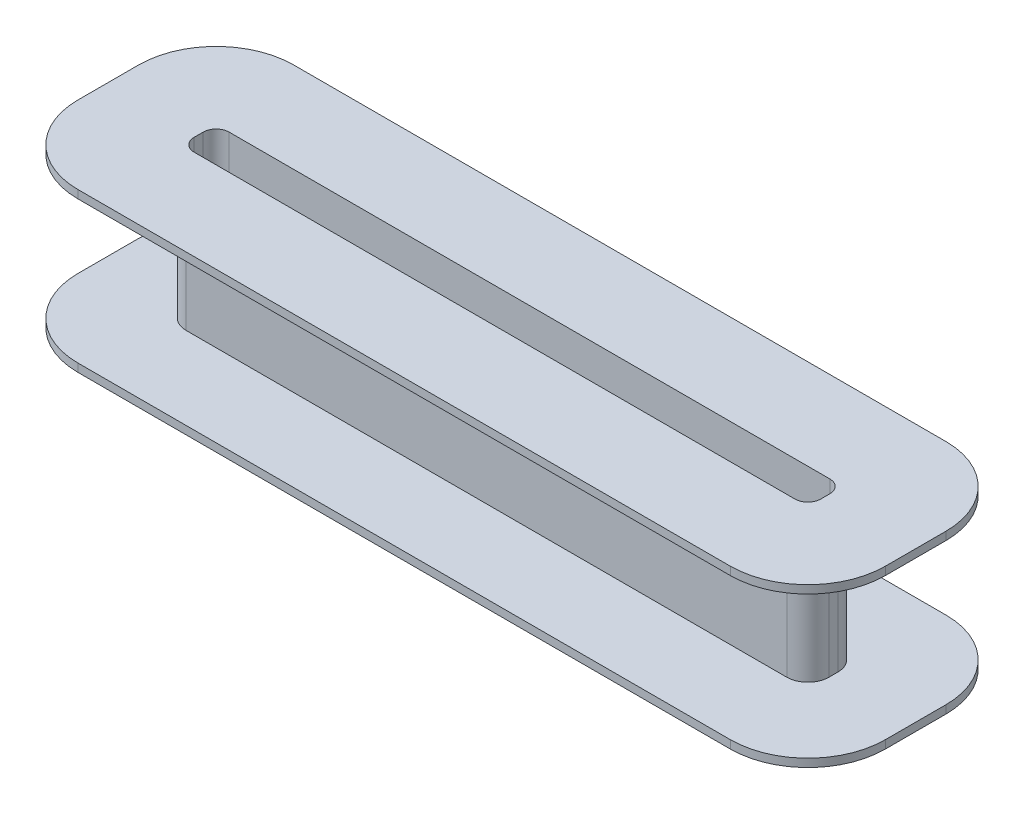
SolidWorks part; units mm, degrees
ref_plane "Front Plane" through (0, 0, 0) normal (0, 0, 1) x (1, 0, 0)
ref_plane "Top Plane" through (0, 0, 0) normal (0, 1, 0) x (1, 0, 0)
ref_plane "Right Plane" through (0, 0, 0) normal (1, 0, 0) x (0, 0, -1)
sketch "Sketch1" plane through (0, 0, 0) normal (0, 1, 0) x (1, 0, 0)
  line L1 (-30.7975, -1.7145) -> (30.7975, -1.7145)
  line L2 (-30.7975, -1.7145) -> (-30.7975, 1.7145)
  line L3 (-30.7975, 1.7145) -> (30.7975, 1.7145)
  line L4 (30.7975, -1.7145) -> (30.7975, 1.7145)
  line L5 (-30.7975, -1.7145) -> (30.7975, 1.7145) construction
  line L6 (-30.7975, 1.7145) -> (30.7975, -1.7145) construction
  line L7 (-39.6875, -10.6045) -> (39.6875, -10.6045)
  line L8 (-39.6875, -10.6045) -> (-39.6875, 10.6045)
  line L9 (-39.6875, 10.6045) -> (39.6875, 10.6045)
  line L10 (39.6875, -10.6045) -> (39.6875, 10.6045)
  line L11 (-39.6875, -10.6045) -> (39.6875, 10.6045) construction
  line L12 (-39.6875, 10.6045) -> (39.6875, -10.6045) construction
  point P0 (0, 0)
  point P6 (0, 0)
  dimension "D1" = 3.429
  dimension "D2" = 8.89
  dimension "D3" = 8.89
  dimension "D4" = 61.595
extrude "Boss-Extrude1" add sketch "Sketch1" along normal blind 0.8
fillet "Fillet1" radius 1.27 4 edges at (30.7975, 0.4, -1.7145) (30.7975, 0.4, 1.7145) (-30.7975, 0.4, -1.7145) (-30.7975, 0.4, 1.7145)
fillet "Fillet2" radius 7.62 4 edges at (39.6875, 0.4, 10.6045) (39.6875, 0.4, -10.6045) (-39.6875, 0.4, 10.6045) (-39.6875, 0.4, -10.6045)
sketch "Sketch2" plane through (0, 0.8, 0) normal (0, 1, 0) x (1, 0, 0)
  line L0 (29.5275, 1.7145) -> (-29.5275, 1.7145) construction
  line L2 (30.7975, -0.4445) -> (30.7975, 0.4445) construction
  line L8 (-29.5275, -1.7145) -> (29.5275, -1.7145) construction
  line L14 (-30.7975, 0.4445) -> (-30.7975, -0.4445) construction
  line L26 (30.7975, -0.4445) -> (30.7975, 0.4445)
  line L27 (-29.5275, -1.7145) -> (29.5275, -1.7145)
  line L28 (-30.7975, 0.4445) -> (-30.7975, -0.4445)
  line L29 (29.5275, 1.7145) -> (-29.5275, 1.7145)
  line L30 (29.5275, 2.5145) -> (-29.5275, 2.5145)
  line L31 (-31.5975, 0.4445) -> (-31.5975, -0.4445)
  line L32 (-29.5275, -2.5145) -> (29.5275, -2.5145)
  line L33 (31.5975, -0.4445) -> (31.5975, 0.4445)
  arc A0 (-29.5275, 1.7145) -> (-30.7975, 0.4445) centre (-29.5275, 0.4445) ccw construction
  arc A3 (30.7975, 0.4445) -> (29.5275, 1.7145) centre (29.5275, 0.4445) ccw construction
  arc A7 (29.5275, -1.7145) -> (30.7975, -0.4445) centre (29.5275, -0.4445) ccw construction
  arc A16 (-30.7975, -0.4445) -> (-29.5275, -1.7145) centre (-29.5275, -0.4445) ccw construction
  arc A32 (30.7975, 0.4445) -> (29.5275, 1.7145) centre (29.5275, 0.4445) ccw
  arc A33 (29.5275, -1.7145) -> (30.7975, -0.4445) centre (29.5275, -0.4445) ccw
  arc A34 (-30.7975, -0.4445) -> (-29.5275, -1.7145) centre (-29.5275, -0.4445) ccw
  arc A35 (-29.5275, 1.7145) -> (-30.7975, 0.4445) centre (-29.5275, 0.4445) ccw
  arc A36 (-29.5275, 2.5145) -> (-31.5975, 0.4445) centre (-29.5275, 0.4445) ccw
  arc A37 (-31.5975, -0.4445) -> (-29.5275, -2.5145) centre (-29.5275, -0.4445) ccw
  arc A38 (29.5275, -2.5145) -> (31.5975, -0.4445) centre (29.5275, -0.4445) ccw
  arc A39 (31.5975, 0.4445) -> (29.5275, 2.5145) centre (29.5275, 0.4445) ccw
  dimension "D1" = 0.8
extrude "Boss-Extrude2" add sketch "Sketch2" along normal blind 13.97
sketch "Sketch3" plane through (0, 14.77, 0) normal (0, 1, 0) x (1, 0, 0)
  line L0 (29.5275, 1.7145) -> (-29.5275, 1.7145) construction
  line L1 (30.7975, -0.4445) -> (30.7975, 0.4445) construction
  line L2 (-29.5275, -1.7145) -> (29.5275, -1.7145) construction
  line L3 (-30.7975, 0.4445) -> (-30.7975, -0.4445) construction
  line L4 (-32.0675, -10.6045) -> (32.0675, -10.6045)
  line L5 (39.6875, -2.9845) -> (39.6875, 2.9845)
  line L6 (32.0675, 10.6045) -> (-32.0675, 10.6045)
  line L7 (-39.6875, 2.9845) -> (-39.6875, -2.9845)
  line L8 (-32.0675, -10.6045) -> (32.0675, -10.6045)
  line L9 (39.6875, -2.9845) -> (39.6875, 2.9845)
  line L10 (32.0675, 10.6045) -> (-32.0675, 10.6045)
  line L11 (-39.6875, 2.9845) -> (-39.6875, -2.9845)
  line L12 (29.5275, 1.7145) -> (-29.5275, 1.7145)
  line L13 (30.7975, -0.4445) -> (30.7975, 0.4445)
  line L14 (-29.5275, -1.7145) -> (29.5275, -1.7145)
  line L15 (-30.7975, 0.4445) -> (-30.7975, -0.4445)
  arc A0 (30.7975, 0.4445) -> (29.5275, 1.7145) centre (29.5275, 0.4445) ccw construction
  arc A1 (29.5275, -1.7145) -> (30.7975, -0.4445) centre (29.5275, -0.4445) ccw construction
  arc A2 (-30.7975, -0.4445) -> (-29.5275, -1.7145) centre (-29.5275, -0.4445) ccw construction
  arc A3 (-29.5275, 1.7145) -> (-30.7975, 0.4445) centre (-29.5275, 0.4445) ccw construction
  arc A4 (32.0675, -10.6045) -> (39.6875, -2.9845) centre (32.0675, -2.9845) ccw
  arc A5 (39.6875, 2.9845) -> (32.0675, 10.6045) centre (32.0675, 2.9845) ccw
  arc A6 (-32.0675, 10.6045) -> (-39.6875, 2.9845) centre (-32.0675, 2.9845) ccw
  arc A7 (-39.6875, -2.9845) -> (-32.0675, -10.6045) centre (-32.0675, -2.9845) ccw
  arc A8 (32.0675, -10.6045) -> (39.6875, -2.9845) centre (32.0675, -2.9845) ccw
  arc A9 (39.6875, 2.9845) -> (32.0675, 10.6045) centre (32.0675, 2.9845) ccw
  arc A10 (-32.0675, 10.6045) -> (-39.6875, 2.9845) centre (-32.0675, 2.9845) ccw
  arc A11 (-39.6875, -2.9845) -> (-32.0675, -10.6045) centre (-32.0675, -2.9845) ccw
  arc A12 (30.7975, 0.4445) -> (29.5275, 1.7145) centre (29.5275, 0.4445) ccw
  arc A13 (29.5275, -1.7145) -> (30.7975, -0.4445) centre (29.5275, -0.4445) ccw
  arc A14 (-30.7975, -0.4445) -> (-29.5275, -1.7145) centre (-29.5275, -0.4445) ccw
  arc A15 (-29.5275, 1.7145) -> (-30.7975, 0.4445) centre (-29.5275, 0.4445) ccw
  dimension "D1" = 0
extrude "Boss-Extrude3" add sketch "Sketch3" along normal blind 0.8
